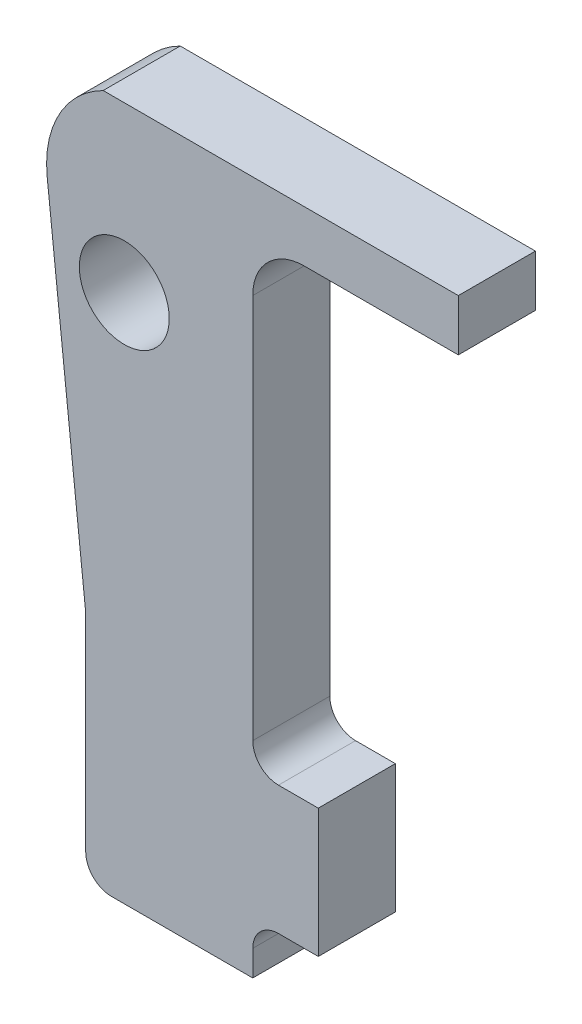
SolidWorks part; units mm, degrees
ref_plane "Plan de face" through (0, 0, 0) normal (0, 0, 1) x (1, 0, 0)
ref_plane "Plan de dessus" through (0, 0, 0) normal (0, 1, 0) x (1, 0, 0)
ref_plane "Plan de droite" through (0, 0, 0) normal (1, 0, 0) x (0, 0, -1)
sketch "Esquisse1" plane through (0, 0, 0) normal (0, 0, 1) x (1, 0, 0)
  line L0 (3.1773, 17) -> (17, 17)
  line L1 (17, 17) -> (17, 15)
  line L2 (17, 15) -> (11, 15)
  line L4 (9, 13) -> (9, -2)
  line L5 (10, -3) -> (11.55, -3)
  line L7 (11.55, -8) -> (10, -8)
  line L8 (9, -9) -> (9, -10)
  line L9 (9, -10) -> (3.5, -10)
  line L10 (2.5, -9) -> (2.5, -1)
  line L11 (2.4943, -0.8931) -> (1, 13)
  line L12 (-2, 17.5) -> (10, 17.5) construction
  line L13 (11.55, -3) -> (11.55, -8)
  line L14 (10, -12.5) -> (10, 17.5) construction
  line L15 (11.55, 10.2) -> (11.55, -10.2) construction
  circle A0 centre (4, 10.6) radius 1.6 construction
  circle A1 centre (4, 10.6) radius 1.6 construction
  circle A2 centre (4, 10.6) radius 1.75
  arc A3 (1, 13) -> (3.1773, 17) centre (4.9771, 13.4278) cw
  arc A4 (11, 15) -> (9, 13) centre (11, 13) ccw
  arc A5 (2.5, -1) -> (2.4943, -0.8931) centre (1.5, -1) ccw
  arc A6 (3.5, -10) -> (2.5, -9) centre (3.5, -9) cw
  arc A7 (10, -8) -> (9, -9) centre (10, -9) ccw
  arc A8 (9, -2) -> (10, -3) centre (10, -2) ccw
  point P35 (17, 16)
  dimension "D2" = 2
  dimension "D3" = 1
  dimension "D9" = 1
  dimension "D11" = 4
  dimension "D4" = 0.5
  dimension "D5" = 2
  dimension "D7" = 18
  dimension "D8" = 27
  dimension "D10" = 6.5
  dimension "D12" = 1.5
  dimension "D13" = 4
  dimension "D14" = 14
  dimension "D16" = 8
  dimension "D1" = 0.15
extrude "Boss.-Extru.1" add sketch "Esquisse1" along normal blind 3
